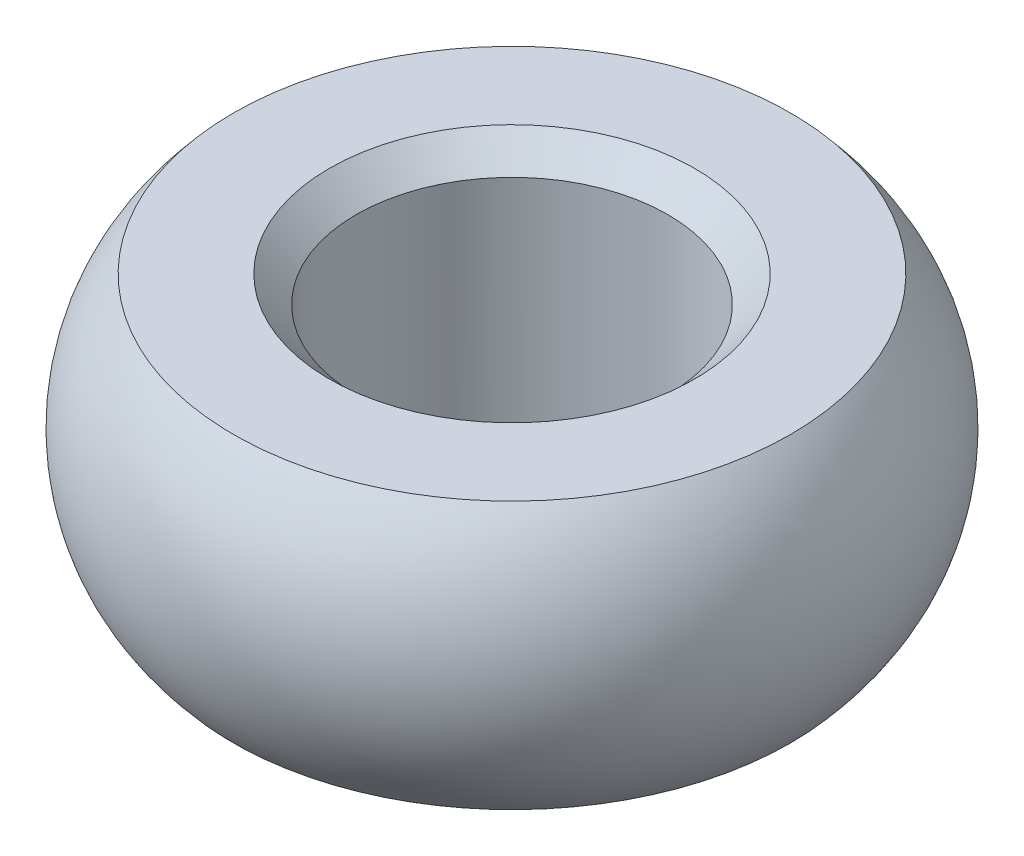
SolidWorks part; units mm, degrees
material "Custom Plastic"
ref_plane "Front Plane" through (0, 0, 0) normal (0, 0, 1) x (1, 0, 0)
ref_plane "Top Plane" through (0, 0, 0) normal (0, 1, 0) x (1, 0, 0)
ref_plane "Right Plane" through (0, 0, 0) normal (1, 0, 0) x (0, 0, -1)
sketch "Sketch1" plane through (0, 0, 0) normal (0, 0, 1) x (1, 0, 0)
  line L0 (0, -562.8227) -> (0, 27578.3136) construction
  line L1 (17.5, 15) -> (17.5, -15)
  line L2 (17.5, -15) -> (31.2705, -15)
  line L3 (17.5, 15) -> (31.2705, 15)
  arc A0 (31.2705, 15) -> (31.2705, -15) centre (14.5, 0) cw
  point P5 (17.5, 0)
  point P9 (37, 0)
  dimension "D3" = 22.5
  dimension "D1" = 30
  dimension "D2" = 17.5
  dimension "D4" = 74
revolve "Revolve1" add sketch "Sketch1" angle 360 about L0
chamfer "Chamfer1" distance 3 angle 45 2 edges at (17.5, 15, 0) (17.5, -15, 0)
